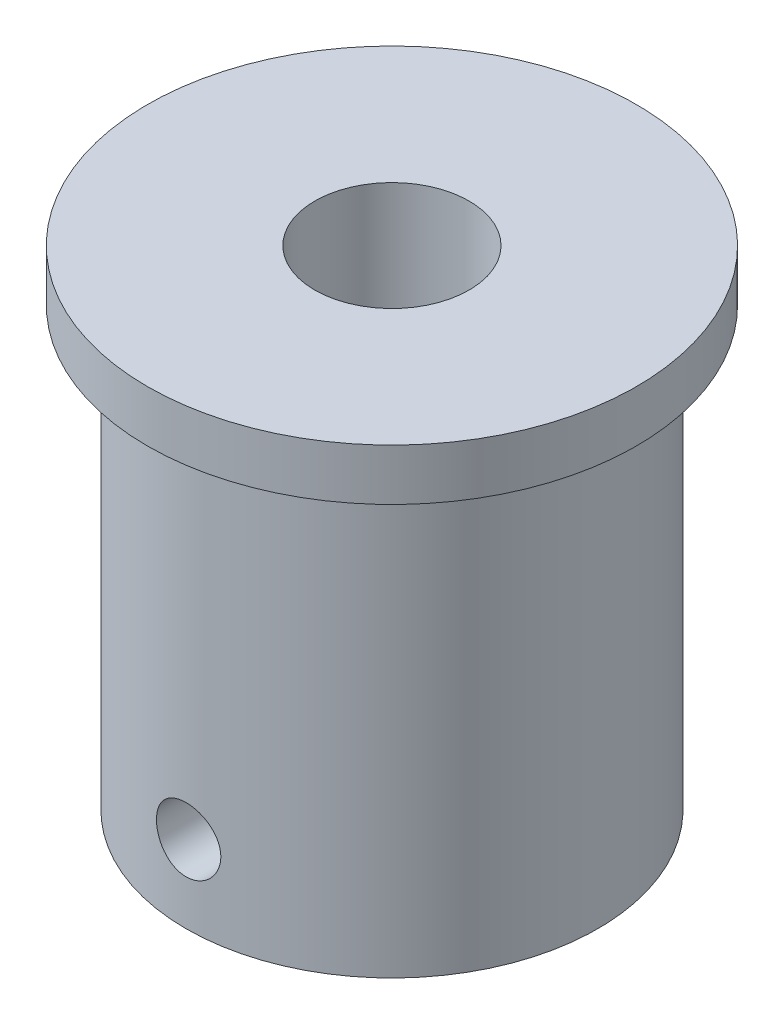
SolidWorks part; units mm, degrees
ref_plane "Front Plane" through (0, 0, 0) normal (0, 0, 1) x (1, 0, 0)
ref_plane "Top Plane" through (0, 0, 0) normal (0, 1, 0) x (1, 0, 0)
ref_plane "Right Plane" through (0, 0, 0) normal (1, 0, 0) x (0, 0, -1)
sketch "Sketch1" plane through (0, 0, 0) normal (0, 1, 0) x (1, 0, 0)
  circle A0 centre (0, 0) radius 4
  dimension "D1" = 8
extrude "Boss-Extrude1" add sketch "Sketch1" along normal blind 8.5
sketch "Sketch2" plane through (0, 8.5, 0) normal (0, 1, 0) x (1, 0, 0)
  circle A0 centre (0, 0) radius 4.75
  dimension "D1" = 9.5
extrude "Boss-Extrude2" add sketch "Sketch2" along normal blind 1
hole_wizard "M1.6 Tapped Hole1" [suppressed] positions "Sketch3" profile "Sketch4" tap size "M1.6" standard "ISO"
sketch "Sketch3" plane through (0, 5, 0) normal (0, 1, 0) x (1, 0, 0)
  point P0 (0, 0)
sketch "Sketch4" plane through (0, 5, 0) normal (1, 0, 0) x (0, 0, 1)
  line L0 (0, 0) -> (0, 5)
  line L1 (0, 5) -> (0.625, 5)
  line L2 (0.625, 5) -> (0.625, 0)
  line L5 (0.625, 0) -> (0, 0)
  line L11 (0, -6.35) -> (0, 107.95) construction
  dimension "Thru Tap Drill Dia." = 1.25
  dimension "Thru Tap Drill Depth" = 5
cosmetic thread "Hole Thread1" [suppressed] parameters "D2"=1.6
sketch "Sketch5" plane through (0, 9.5, 0) normal (0, 1, 0) x (1, 0, 0)
  line L0 (0, 0.1941) -> (0, 2.6435) construction
  line L1 (1, 2.6435) -> (-1, 2.6435)
  line L2 (-1, 2.6435) -> (-1, 4.6435)
  line L3 (1, 2.6435) -> (1, 4.6435)
  arc A0 (1, 4.6435) -> (-1, 4.6435) centre (0, 0) ccw
  circle A1 centre (0, 0) radius 4.75 construction
  dimension "D1" = 2
  dimension "D2" = 1
extrude "Cut-Extrude1" [suppressed] cut sketch "Sketch5" against normal through all
hole_wizard "M1.6 Tapped Hole2" [suppressed] positions "Sketch6" profile "Sketch7" tap size "M1.6" standard "ISO"
sketch "Sketch6" plane through (0, 5, 0) normal (0, 1, 0) x (1, 0, 0)
  line L0 (-4.75, 0) -> (4.75, 0)
  circle A0 centre (0, 0) radius 4.75 construction
  point P7 (-3.25, 0)
  point P9 (3.25, 0)
  dimension "D1" = 1.5
  dimension "D2" = 1.5
sketch "Sketch7" plane through (3.25, 5, 0) normal (1, 0, 0) x (0, 0, 1)
  line L0 (0, 0) -> (0, 5)
  line L1 (0, 5) -> (0.625, 5)
  line L2 (0.625, 5) -> (0.625, 0)
  line L5 (0.625, 0) -> (0, 0)
  line L11 (0, -6.35) -> (0, 107.95) construction
  dimension "Thru Tap Drill Dia." = 1.25
  dimension "Thru Tap Drill Depth" = 5
cosmetic thread "Hole Thread2" [suppressed] parameters "D2"=1.6
cosmetic thread "Hole Thread3" [suppressed] parameters "D2"=1.6
sketch "Sketch8" plane through (0, 9.5, 0) normal (0, 1, 0) x (1, 0, 0)
  circle A0 centre (0, 0) radius 1.5
  dimension "D1" = 3
extrude "Cut-Extrude2" cut sketch "Sketch8" against normal through all
ref_plane "Plane1" through (0, 0, -5) normal (0, 0, 1) x (1, 0, 0)
hole_wizard "M1.6 Tapped Hole4" positions "Sketch10" profile "Sketch9" tap size "M1.6" standard "ISO" end condition through all
sketch "Sketch10" plane through (0, 0, -5) normal (0, 0, 1) x (1, 0, 0)
  point P1 (0, 1.5)
  dimension "D1" = 1.5
sketch "Sketch9" plane through (0, 1.5, -5) normal (1, 0, 0) x (0, 1, 0)
  line L0 (0, 0) -> (0, 9.75)
  line L1 (0, 9.75) -> (0.625, 9.75)
  line L2 (0.625, 9.75) -> (0.625, 0)
  line L5 (0.625, 0) -> (0, 0)
  line L11 (0, -6.35) -> (0, 107.95) construction
  dimension "Thru Tap Drill Dia." = 1.25
  dimension "Thru Tap Drill Depth" = 9.75
cosmetic thread "Hole Thread4" parameters "D2"=1.6
